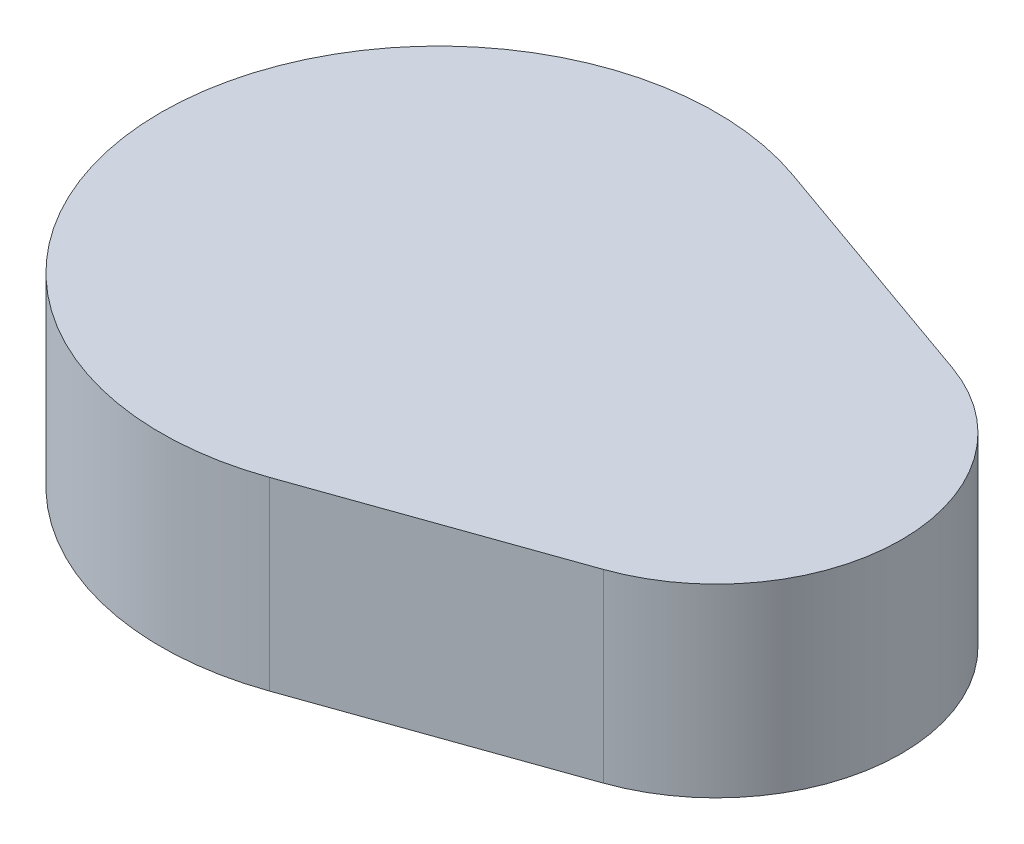
SolidWorks part; units mm, degrees
ref_plane "前视基准面" through (0, 0, 0) normal (0, 0, 1) x (1, 0, 0)
ref_plane "上视基准面" through (0, 0, 0) normal (0, 1, 0) x (1, 0, 0)
ref_plane "右视基准面" through (0, 0, 0) normal (1, 0, 0) x (0, 0, -1)
sketch "草图1" plane through (0, 0, 0) normal (0, 1, 0) x (1, 0, 0)
  line L0 (5, -14.1421) -> (18.3333, -9.4281)
  line L1 (5, 14.1421) -> (18.3333, 9.4281)
  line L2 (0, 0) -> (15, 0) construction
  arc A0 (5, 14.1421) -> (5, -14.1421) centre (0, 0) ccw
  arc A1 (18.3333, 9.4281) -> (18.3333, -9.4281) centre (15, 0) cw
  point P7 (0, 0)
  point P8 (0, 0)
  dimension "D1" = 15
  dimension "D2" = 10
  dimension "D3" = 15
extrude "凸台-拉伸1" add sketch "草图1" along normal blind 10
